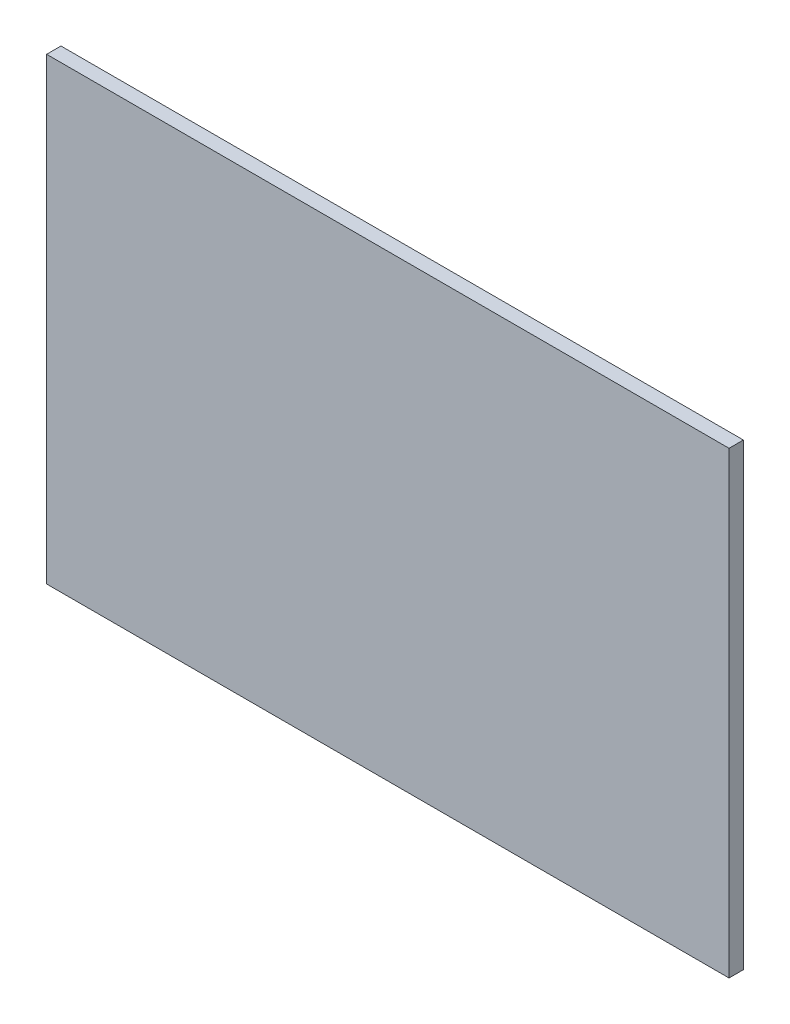
SolidWorks part; units mm, degrees
ref_plane "Front Plane" through (0, 0, 0) normal (0, 0, 1) x (1, 0, 0)
ref_plane "Top Plane" through (0, 0, 0) normal (0, 1, 0) x (1, 0, 0)
ref_plane "Right Plane" through (0, 0, 0) normal (1, 0, 0) x (0, 0, -1)
sketch "Sketch1" plane through (0, 0, 0) normal (0, 0, 1) x (1, 0, 0)
  line L1 (75.565, -50.8) -> (-75.565, -50.8)
  line L2 (75.565, -50.8) -> (75.565, 50.8)
  line L3 (75.565, 50.8) -> (-75.565, 50.8)
  line L4 (-75.565, -50.8) -> (-75.565, 50.8)
  line L5 (75.565, -50.8) -> (-75.565, 50.8) construction
  line L6 (75.565, 50.8) -> (-75.565, -50.8) construction
  point P0 (0, 0)
  dimension "D1" = 151.13
  dimension "D2" = 101.6
extrude "Boss-Extrude1" add sketch "Sketch1" along normal blind 3.175
